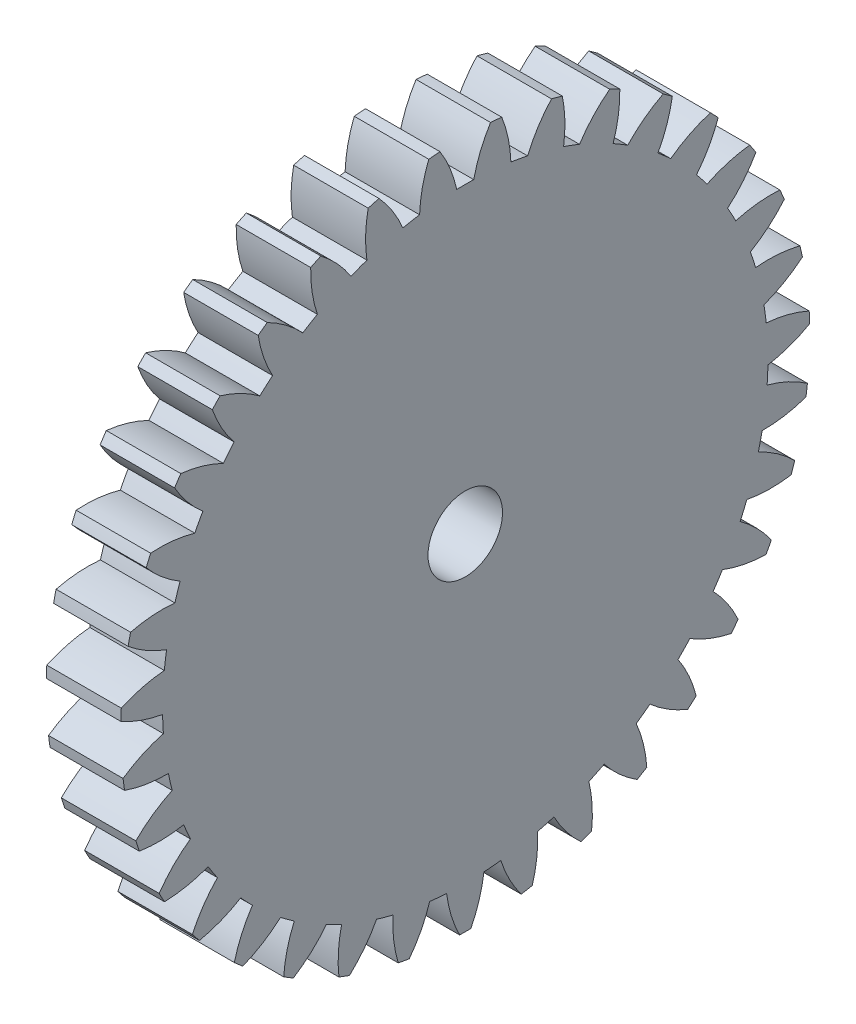
SolidWorks part; units mm, degrees
ref_plane "Plane1" through (0, 0, 0) normal (0, 0, 1) x (1, 0, 0)
ref_plane "Plane2" through (0, 0, 0) normal (0, 1, 0) x (1, 0, 0)
ref_plane "Plane3" through (0, 0, 0) normal (1, 0, 0) x (0, 0, -1)
other "Configuration Table"
sketch "HoldingSke" plane through (0, 0, 0) normal (0, 1, 0) x (1, 0, 0)
  line L0 (0, 0) -> (0.8192, -0.5736)
  line L1 (-15, 0) -> (100, 0) construction
  line L2 (0, 0) -> (-2.1039, 2.3779)
  line L3 (0, 0) -> (-11.863, 4.5341)
  line L4 (0, 0) -> (7.0742, 4.9534)
  line L5 (0, 0) -> (-46.8476, -17.4728)
  line L6 (0, 0) -> (-3.3159, -2.2372)
  line L7 (-2.1039, 2.3779) -> (8.6586, 51.2059)
  line L8 (-76.2, 54.61) -> (-75.5, 54.61)
  line L9 (-71.009, 38.7566) -> (-53.1078, 45.2721)
  line L10 (-76.2, 71.12) -> (104.1128, 71.12)
  line L11 (0, 0) -> (-4, 0)
  line L12 (-76.2, 101.6) -> (-76.162, 101.6)
  line L13 (24.9733, 27.94) -> (52.9518, 28.4284)
  line L14 (24.9733, 27.94) -> (24.9743, 27.94)
  line L15 (24.9733, 27.94) -> (100.4006, 29.5858)
  line L16 (-63.627, -1) -> (-12.827, -1)
  circle A0 centre (0, 0) radius 2
  circle A1 centre (0, 0) radius 16.249
  circle A2 centre (0, 0) radius 37.5
  circle A3 centre (0, 0) radius 2
  dimension "MHD" = 32.498
  dimension "Hub_dia" = 75
  dimension "Bore" = 4
  dimension "MBD" = 4
  dimension "Num_teeth" = 35
  dimension "Pitch" = 1
  dimension "Overall_len" = 50
  dimension "Show_teeth" = 35
  dimension "Thickness" = 4
  dimension "OAL" = 50.0001
  dimension "T_dim" = 0.7
  dimension "Ap" = 20
  dimension "H" = 19.05
  dimension "Pitch_radius" = 180.3128
  dimension "Width" = 4
  dimension "Backlash" = 0.038
  dimension "Addendum_fac" = 1
  dimension "Dedendum_fac" = 1.25
  dimension "Clearance_fac" = 0.25
  dimension "Dedendum_add" = 0.001
  dimension "Module" = 1
sketch "BasProSke" plane through (0, 0, 0) normal (0, 1, 0) x (1, 0, 0)
  line L0 (-10, 0) -> (60, 0) construction
  line L1 (0, 0) -> (0, 18.5)
  line L2 (0, 0) -> (4, 0)
  line L3 (4, 0) -> (4, 18.5)
  line L4 (4, 18.5) -> (0, 18.5)
  dimension "Thickness" = 4
  dimension "Diameter" = 37
revolve "Base-Revolve" add sketch "BasProSke" angle 360 about L0
sketch "TooCutSke" plane through (0, 0, 0) normal (1, 0, 0) x (0, 0, -1)
  line L1 (0, 0) -> (0, 107) construction
  line L2 (0, 0) -> (-0.8516, 17.4793) construction
  line L3 (0, 0) -> (-3.1347, 34.8297) construction
  line L4 (-0.8516, 17.4793) -> (-1.5674, 17.4148) construction
  arc A0 (0.4564, 16.2426) -> (-0.4564, 16.2426) centre (0, 0) ccw
  arc A1 (1.373, 18.4745) -> (-1.373, 18.4745) centre (0, 0) ccw
  circle A2 centre (0, 0) radius 17.5 construction
  circle A3 centre (0, 0) radius 16.4446 construction
  arc A4 (-0.4564, 16.2426) -> (-1.373, 18.4745) centre (-7.293, 14.739) ccw
  arc A5 (1.373, 18.4745) -> (0.4564, 16.2426) centre (7.293, 14.739) ccw
  dimension "Root_dia" = 32.498
  dimension "Overcut_dia" = 37.0508
  dimension "Pitch_dia" = 35
  dimension "Base_dia" = 32.8892
  dimension "Flank_rad" = 7
  dimension "Half_ang" = 5.143
  dimension "Half_CT" = 0.7186
extrude "ToothCut" cut sketch "TooCutSke" along normal through all
fillet "Breaks" [suppressed] radius 0.02
fillet "RootFillets" [suppressed] radius 0.251
pattern_circular "TeethCuts" count 35 every 10.286 about axis through (-10, 0, 0) along (1, 0, 0) of "ToothCut", "RootFillets", "Breaks"
sketch "HubNeaOneSke" plane through (0, 0, 0) normal (-1, 0, 0) x (0, 0, 1)
  circle A0 centre (0, 0) radius 16.249
  dimension "Diameter" = 32.498
extrude "HubNearOne" [suppressed] add sketch "HubNeaOneSke" along normal blind 46.0001
sketch "HubNeaBotSke" plane through (0, 0, 0) normal (-1, 0, 0) x (0, 0, 1)
  circle A0 centre (0, 0) radius 16.249
  dimension "Diameter" = 32.498
extrude "HubNearBoth" [suppressed] add sketch "HubNeaBotSke" along normal blind 23
ref_plane "FarPln" through (4, 0, 0) normal (1, 0, 0) x (0, 0, -1)
sketch "HubFarSke" plane through (4, 0, 0) normal (1, 0, 0) x (0, 0, -1)
  circle A0 centre (0, 0) radius 16.249
  dimension "Diameter" = 32.498
extrude "HubFar" [suppressed] add sketch "HubFarSke" along normal blind 23
sketch "BorSke" plane through (0, 0, 0) normal (1, 0, 0) x (0, 0, -1)
  circle A0 centre (0, 0) radius 2
  dimension "Diameter" = 4
extrude "Bore" cut sketch "BorSke" along normal mid plane 100.0001
sketch "KeySke" plane through (0, 0, 0) normal (1, 0, 0) x (0, 0, -1)
  line L0 (-0.8, 0) -> (-0.8, 2.7)
  line L1 (-0.8, 2.7) -> (0.8, 2.7)
  line L2 (0.8, 2.7) -> (0.8, 0)
  line L3 (0, 0) -> (0, 34) construction
  line L4 (-0.8, 0) -> (0.8, 0)
  dimension "Offset" = 2.7
  dimension "Width" = 1.6
extrude "Keyway" [suppressed] cut sketch "KeySke" along normal mid plane 100.0001
pattern_circular "Keyway2" [suppressed] count 2 every 90 about axis through (-10, 0, 0) along (1, 0, 0)
equation "' \"Module@HoldingSke\" = 6.35"
equation "' \"Num_teeth@HoldingSke\" = 12"
equation "' \"Ap@HoldingSke\" =  20"
equation "' \"Ap@HoldingSke\" = 20"
equation "' \"Width@HoldingSke\" = 0.5 * 25.4"
equation "' \"Hub_dia@HoldingSke\"= 1 * 25.4"
equation "' \"Hub_dia@HoldingSke\" = 1 * 25.4"
equation "' \"Overall_len@HoldingSke\" = 1.0 * 25.4"
equation "' \"Bore@HoldingSke\" = 0.75 * 25.4"
equation "' \"T_dim@HoldingSke\" = 0.1 * 25.4"
equation "' \"Width@KeySke\" = 0.25 * 25.4"
equation "' \"Show_teeth@HoldingSke\" = 13"
equation "' \"Backlash@HoldingSke\" = 0.009 * 25.4"
equation "' \"Addendum_fac@HoldingSke\" = 1.0"
equation "' \"Dedendum_fac@HoldingSke\" = 1.25"
equation "' \"Dedendum_add@HoldingSke\" = 0.00005 * 25.4"
equation "' \"Clearance_fac@HoldingSke\" = 0.25"
equation "\"Pitch@HoldingSke\" = 1 / \"Module@HoldingSke\""
equation "\"Overcut_dia@TooCutSke\" = (\"Num_teeth@HoldingSke\" + 2 * \"Addendum_fac@HoldingSke\") / \"Pitch@HoldingSke\" + 0.002 * 25.4"
equation "\"Pitch_dia@TooCutSke\" = \"Num_teeth@HoldingSke\" / \"Pitch@HoldingSke\""
equation "\"Base_dia@TooCutSke\" = \"Num_teeth@HoldingSke\" / \"Pitch@HoldingSke\" * cos((\"Ap@HoldingSke\"  * 3.14159265 / 180))"
equation "\"Root_dia@TooCutSke\" = (\"Num_teeth@HoldingSke\" + 2) / \"Pitch@HoldingSke\" - 2 * (\"Addendum_fac@HoldingSke\" + \"Dedendum_fac@HoldingSke\") / \"Pitch@HoldingSke\" - \"Dedendum_add@HoldingSke\" * 2"
equation "\"Half_ang@TooCutSke\" = 180 / \"Num_teeth@HoldingSke\""
equation "\"Half_CT@TooCutSke\" = \"Num_teeth@HoldingSke\" / \"Pitch@HoldingSke\" * sin((3.14159265 / 2 / \"Num_teeth@HoldingSke\")) / 2 - 7 * \"Backlash@HoldingSke\" / 4"
equation "\"Flank_rad@TooCutSke\" = \"Num_teeth@HoldingSke\" / \"Pitch@HoldingSke\" / 5"
equation "\"Radius@RootFillets\" = \"Clearance_fac@HoldingSke\" / \"Pitch@HoldingSke\" + \"Dedendum_add@HoldingSke\""
equation "\"Break_rad@Breaks\" = 0.02 / \"Pitch@HoldingSke\""
equation "\"Thickness@HoldingSke\" = \"Width@HoldingSke\""
equation "\"OAL@HoldingSke\" = \"Thickness@HoldingSke\""
equation "\"MHD@HoldingSke\" = (\"Num_teeth@HoldingSke\" + 2) / \"Pitch@HoldingSke\" - 2 * (\"Addendum_fac@HoldingSke\" + \"Dedendum_fac@HoldingSke\")  / \"Pitch@HoldingSke\" - \"Dedendum_add@HoldingSke\" * 2"
equation "\"MBD@HoldingSke\" = (\"Num_teeth@HoldingSke\" + 2) / \"Pitch@HoldingSke\" - 2 * (\"Addendum_fac@HoldingSke\" + \"Dedendum_fac@HoldingSke\")  / \"Pitch@HoldingSke\" - \"Dedendum_add@HoldingSke\" * 2 - 0.002 * 25.4"
equation "\"MHD@HoldingSke\" = ((sgn( \"MHD@HoldingSke\" - \"Hub_dia@HoldingSke\" )-1)*( \"MHD@HoldingSke\" - \"Hub_dia@HoldingSke\" ))/-2+ \"Hub_dia@HoldingSke\""
equation "\"MBD@HoldingSke\" = ((sgn( \"MBD@HoldingSke\" - \"Bore@HoldingSke\" )-1)*( \"MBD@HoldingSke\" - \"Bore@HoldingSke\" ))/-2+ \"Bore@HoldingSke\""
equation "\"OAL@HoldingSke\" = ((sgn( \"OAL@HoldingSke\" - \"Overall_len@HoldingSke\" )+1)*( \"OAL@HoldingSke\" - \"Overall_len@HoldingSke\" ))/2 + \"Overall_len@HoldingSke\" + 0.000002 * 25.4"
equation "\"Num_teeth@TeethCuts\" = int( \"Show_teeth@HoldingSke\" ) + 1"
equation "\"Num_teeth@TeethCuts\" = ((sgn( \"Num_teeth@TeethCuts\" - \"Num_teeth@HoldingSke\" )-1)*( \"Num_teeth@TeethCuts\" - \"Num_teeth@HoldingSke\" ))/-2+ \"Num_teeth@HoldingSke\""
equation "\"Num_teeth@TeethCuts\" = ((sgn( \"Num_teeth@TeethCuts\" - 2.0)+1)*( \"Num_teeth@TeethCuts\" - 2.0))/2 +2.0"
equation "\"Angle@TeethCuts\" = 360.0 / \"Num_teeth@HoldingSke\""
equation "\"Diameter@BasProSke\" = (\"Num_teeth@HoldingSke\" + 2 * \"Addendum_fac@HoldingSke\") / \"Pitch@HoldingSke\""
equation "\"Thickness@BasProSke\"  = \"Thickness@HoldingSke\""
equation "' \"Fillet_rad@BasProSke\" =  \"Thickness@HoldingSke\" * 0.05"
equation "' \"Fillet_rad@BasProSke\" = \"Thickness@HoldingSke\" * 0.05"
equation "\"MHD@HoldingSke\" = ((sgn( \"MHD@HoldingSke\" - \"Root_dia@TooCutSke\" )-1)*( \"MHD@HoldingSke\" - \"Root_dia@TooCutSke\" ))/-2+ \"Root_dia@TooCutSke\""
equation "\"Diameter@HubNeaOneSke\" = \"MHD@HoldingSke\""
equation "\"Length@HubNearOne\" = \"OAL@HoldingSke\" - \"Thickness@BasProSke\""
equation "\"Diameter@HubNeaBotSke\" = \"MHD@HoldingSke\""
equation "\"Length@HubNearBoth\" = ( \"OAL@HoldingSke\" - \"Thickness@BasProSke\" ) / 2.0"
equation "\"Thickness@FarPln\" = \"Thickness@BasProSke\""
equation "\"Diameter@HubFarSke\" = \"MHD@HoldingSke\""
equation "\"Length@HubFar\" = ( \"OAL@HoldingSke\" - \"Thickness@BasProSke\" ) / 2.0"
equation "\"Diameter@BorSke\" = \"MBD@HoldingSke\""
equation "\"D1@Bore\" = \"OAL@HoldingSke\" * 2.0"
equation "\"D1@Keyway\" = \"OAL@HoldingSke\" * 2.0"
equation "\"Offset@KeySke\" = \"T_dim@HoldingSke\" + \"MBD@HoldingSke\" / 2.0"
